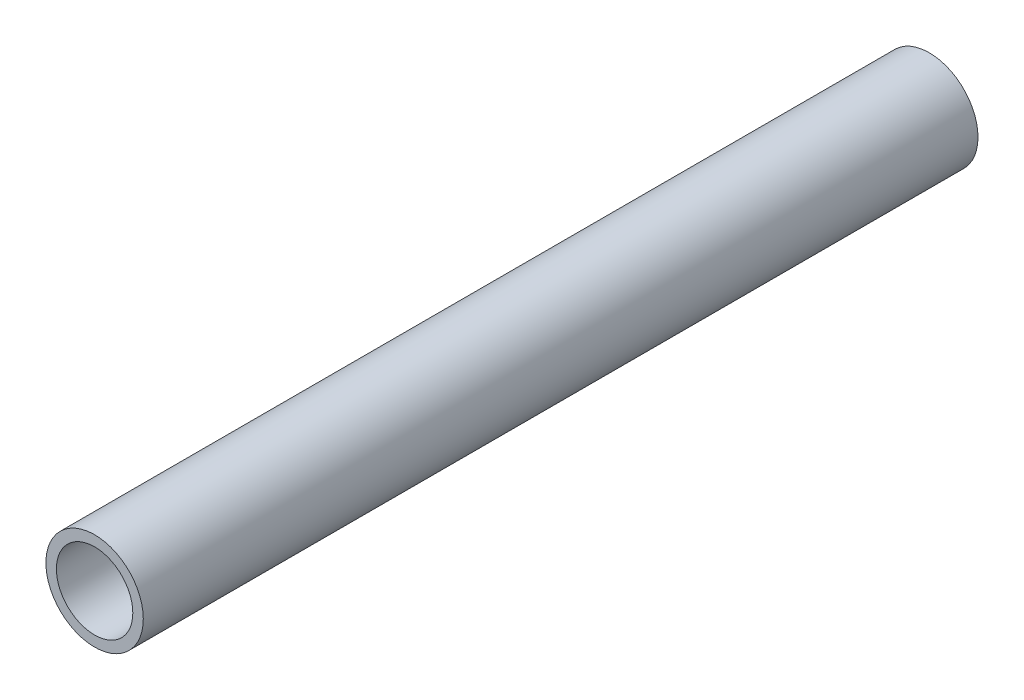
SolidWorks part; units mm, degrees
ref_plane "Front Plane" through (0, 0, 0) normal (0, 0, 1) x (1, 0, 0)
ref_plane "Top Plane" through (0, 0, 0) normal (0, 1, 0) x (1, 0, 0)
ref_plane "Right Plane" through (0, 0, 0) normal (1, 0, 0) x (0, 0, -1)
sketch "Sketch1" plane through (0, 0, 0) normal (0, 0, 1) x (1, 0, 0)
  circle A0 centre (0, 0) radius 10.4648
  circle A1 centre (0, 0) radius 13.335
  dimension "D1" = 2.8702
  dimension "D2" = 26.67
extrude "Boss-Extrude1" add sketch "Sketch1" along normal blind 228.6
